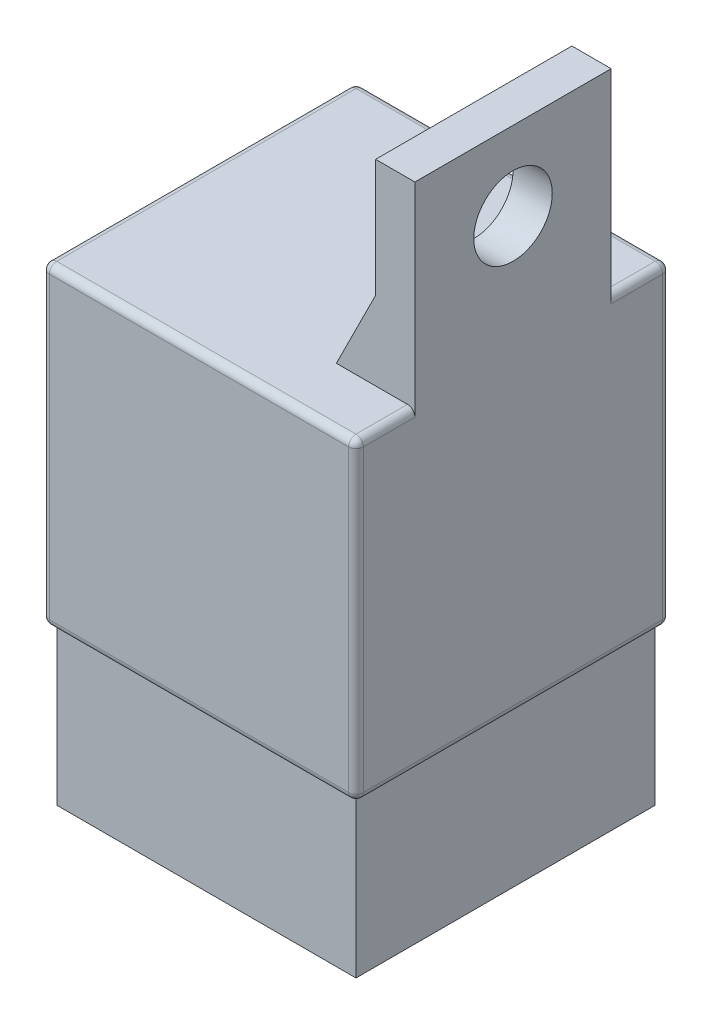
SolidWorks part; units mm, degrees
ref_plane "Front Plane" through (0, 0, 0) normal (0, 0, 1) x (1, 0, 0)
ref_plane "Top Plane" through (0, 0, 0) normal (0, 1, 0) x (1, 0, 0)
ref_plane "Right Plane" through (0, 0, 0) normal (1, 0, 0) x (0, 0, -1)
sketch "Sketch1" plane through (0, 0, 0) normal (0, 0, 1) x (1, 0, 0)
  line L1 (0, 0) -> (-25.4, 0)
  line L2 (0, 0) -> (0, 25.4)
  line L3 (0, 25.4) -> (-25.4, 25.4)
  line L4 (-25.4, 0) -> (-25.4, 25.4)
  dimension "D1" = 25.4
  dimension "D2" = 25.4
extrude "Boss-Extrude1" add sketch "Sketch1" along normal blind 25.4
sketch "Sketch2" plane through (0, 25.4, 0) normal (0, 1, 0) x (1, 0, 0)
  line L0 (-25.4, -12.7) -> (0, -12.7) construction
  line L1 (-25.4, -25.4) -> (-25.4, 0) construction
  line L2 (0, -25.4) -> (0, 0) construction
  line L4 (-3.175, -20.6375) -> (0, -20.6375)
  line L5 (-3.175, -20.6375) -> (-3.175, -4.7625)
  line L6 (-3.175, -4.7625) -> (0, -4.7625)
  line L7 (0, -20.6375) -> (0, -4.7625)
  line L8 (-3.175, -20.6375) -> (0, -4.7625) construction
  line L9 (-3.175, -4.7625) -> (0, -20.6375) construction
  point P6 (-1.5875, -12.7)
  dimension "D1" = 3.175
  dimension "D2" = 15.875
extrude "Boss-Extrude2" add sketch "Sketch2" along normal blind 15.875
sketch "Sketch6" plane through (0, 0, 20.6375) normal (0, 0, 1) x (1, 0, 0)
  line L0 (-3.175, 25.4) -> (-6.35, 25.4)
  line L1 (-3.175, 41.275) -> (-3.175, 25.4) construction
  line L2 (-6.35, 25.4) -> (-3.175, 31.75)
  line L3 (-3.175, 31.75) -> (-3.175, 25.4)
  dimension "D1" = 3.175
  dimension "D2" = 6.35
extrude "Boss-Extrude3" add sketch "Sketch6" against normal blind 2.54
sketch "Sketch7" plane through (-3.175, 0, 0) normal (-1, 0, 0) x (0, 0, 1)
  line L0 (12.7, 41.275) -> (12.7, 25.4) construction
  line L1 (4.7625, 41.275) -> (20.6375, 41.275) construction
  line L2 (4.7625, 25.4) -> (18.0975, 25.4) construction
ref_plane "Plane1" through (0, 0, 12.7) normal (0, 0, 1) x (1, 0, 0)
mirror "Mirror1" about plane through (0, 0, 12.7) normal (0, 0, 1) of "Boss-Extrude3"
sketch "Sketch8" plane through (-3.175, 0, 0) normal (-1, 0, 0) x (0, 0, 1)
  line L0 (12.7, 25.4) -> (12.7, 41.275) construction
  line L1 (7.3025, 25.4) -> (18.0975, 25.4) construction
  circle A0 centre (12.7, 34.925) radius 3.175
  dimension "D1" = 6.35
  dimension "D2" = 9.525
extrude "Cut-Extrude1" cut sketch "Sketch8" against normal through all
fillet "Fillet1" radius 0.6 13 edges at (-12.7, 25.4, 25.4) (0, 12.7, 25.4) (-25.4, 25.4, 12.7) (-25.4, 12.7, 25.4) (-12.7, 25.4, 0) (-25.4, 12.7, 0) (0, 12.7, 0) (-25.4, 0, 12.7) (-12.7, 0, 25.4) (0, 0, 12.7) (-12.7, 0, 0)
sketch "Sketch9" plane through (0, 0, 0) normal (0, -1, 0) x (-1, 0, 0)
  line L0 (0.6, -24.8) -> (24.8, -24.8) construction
  line L1 (24.8, -24.8) -> (24.8, -0.6) construction
  line L2 (24.8, -0.6) -> (0.6, -0.6) construction
  line L3 (0.6, -0.6) -> (0.6, -24.8) construction
  line L4 (0.6, -24.8) -> (24.8, -24.8)
  line L5 (24.8, -24.8) -> (24.8, -0.6)
  line L6 (24.8, -0.6) -> (0.6, -0.6)
  line L7 (0.6, -0.6) -> (0.6, -24.8)
extrude "Boss-Extrude4" add sketch "Sketch9" along normal blind 12.7
